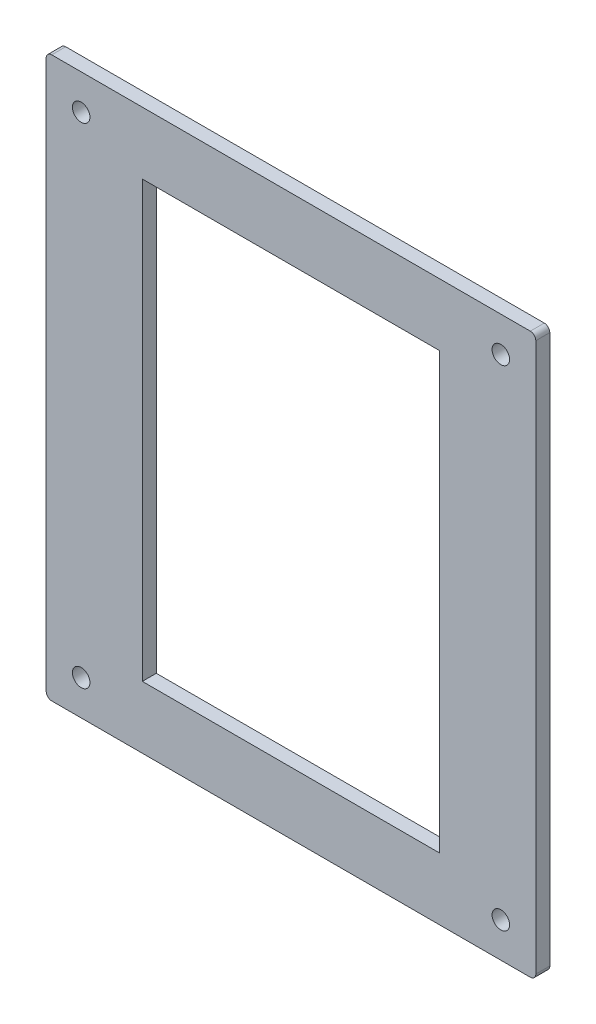
SolidWorks part; units mm, degrees
ref_plane "Front Plane" through (0, 0, 0) normal (0, 0, 1) x (1, 0, 0)
ref_plane "Top Plane" through (0, 0, 0) normal (0, 1, 0) x (1, 0, 0)
ref_plane "Right Plane" through (0, 0, 0) normal (1, 0, 0) x (0, 0, -1)
sketch "Sketch1" plane through (0, 0, 0) normal (0, 0, 1) x (1, 0, 0)
  line L0 (6.35, -6.35) -> (82.55, -6.35) construction
  line L1 (0, 0) -> (88.9, 0)
  line L2 (0, 0) -> (0, -101.6)
  line L3 (0, -101.6) -> (88.9, -101.6)
  line L4 (88.9, 0) -> (88.9, -101.6)
  line L5 (17.45, -11.3) -> (71.45, -11.3)
  line L6 (17.45, -11.3) -> (17.45, -90.3)
  line L7 (17.45, -90.3) -> (71.45, -90.3)
  line L8 (71.45, -11.3) -> (71.45, -90.3)
  line L9 (82.55, -6.35) -> (82.55, -95.25) construction
  line L10 (82.55, -95.25) -> (6.35, -95.25) construction
  line L11 (6.35, -95.25) -> (6.35, -6.35) construction
  line L13 (14.45, -8.3) -> (74.45, -8.3) construction
  line L14 (14.45, -8.3) -> (14.45, -93.3) construction
  line L15 (14.45, -93.3) -> (74.45, -93.3) construction
  line L16 (74.45, -8.3) -> (74.45, -93.3) construction
  circle A0 centre (6.35, -6.35) radius 1.59
  circle A1 centre (82.55, -6.35) radius 1.59
  circle A2 centre (82.55, -95.25) radius 1.59
  circle A3 centre (6.35, -95.25) radius 1.59
  point P17 (44.45, -8.3)
  point P18 (74.45, -50.8)
  point P19 (44.45, 0)
  point P20 (44.45, -6.35)
  point P21 (82.55, -50.8)
  point P22 (88.9, -50.8)
  point P24 (44.45, -11.3)
  point P25 (71.45, -50.8)
  dimension "D3" = 3.18
  dimension "D4" = 76.2
  dimension "D5" = 88.9
  dimension "D6" = 101.6
  dimension "D7" = 85
  dimension "D8" = 60
  dimension "D1" = 3
  dimension "D9" = 79
  dimension "D2" = 3
  dimension "D10" = 54
  dimension "D11" = 88.9
extrude "Boss-Extrude1" add sketch "Sketch1" along normal blind 2.54
fillet "Fillet1" radius 1 4 edges at (0, -101.6, 1.27) (88.9, -101.6, 1.27) (88.9, 0, 1.27) (0, 0, 1.27)
equation "\"D4@Sketch1\"=3.0*25.4"
equation "\"D6@Sketch1\"=4in"
equation "\"D11@Sketch1\"=3.5*25.4"
